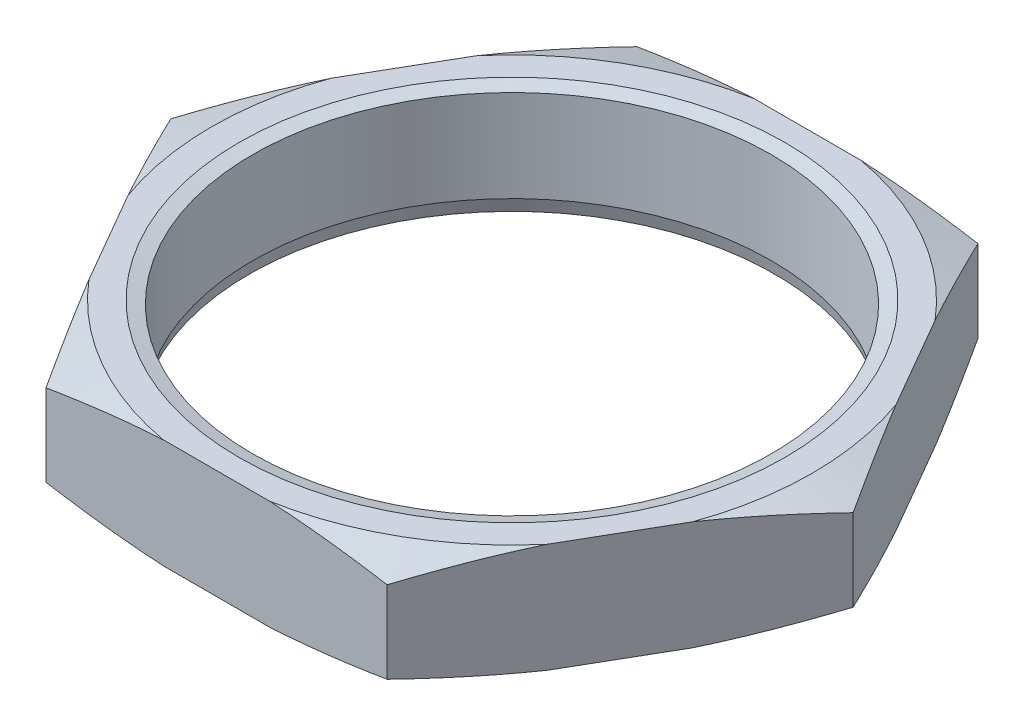
SolidWorks part; units mm, degrees
ref_plane "前视基准面" through (0, 0, 0) normal (0, 0, 1) x (1, 0, 0)
ref_plane "上视基准面" through (0, 0, 0) normal (0, 1, 0) x (1, 0, 0)
ref_plane "右视基准面" through (0, 0, 0) normal (1, 0, 0) x (0, 0, -1)
sketch "草图1" plane through (0, 0, 0) normal (0, 1, 0) x (1, 0, 0)
  line L1 (6.25, 10.8253) -> (-6.25, 10.8253)
  line L2 (-6.25, 10.8253) -> (-12.5, 0)
  line L3 (-12.5, 0) -> (-6.25, -10.8253)
  line L4 (-6.25, -10.8253) -> (6.25, -10.8253)
  line L5 (6.25, -10.8253) -> (12.5, 0)
  line L6 (12.5, 0) -> (6.25, 10.8253)
  circle A0 centre (0, 0) radius 12.5 construction
  circle A1 centre (0, 0) radius 9.5
  dimension "D1" = 25
  dimension "D3" = 19
  dimension "D2" = 21.6506
extrude "凸台-拉伸1" add sketch "草图1" along normal blind 4
sketch "草图2" plane through (0, 0, 0) normal (0, 0, 1) x (1, 0, 0)
  line L0 (11, 4) -> (12.5, 4)
  line L1 (-6.25, 4) -> (6.25, 4) construction
  line L2 (12.5, 4) -> (12.5, 3.5)
  line L4 (12.5, 3.5) -> (11, 4)
  line L5 (12.5, 0.5) -> (12.5, 0)
  line L6 (12.5, 0) -> (11, 0)
  line L7 (-6.25, 0) -> (6.25, 0) construction
  line L8 (11, 0) -> (12.5, 0.5)
  line L9 (0, 0) -> (0, 6.7072) construction
  line L10 (12.5, 4) -> (12.5, 0) construction
  dimension "D1" = 0.5
  dimension "D2" = 1.5
revolve "切除-旋转2" cut sketch "草图2" angle 360 about L9
chamfer "倒角1" distance 0.5 angle 15 2 edges at (0, 4, 9.5) (0, 0, 9.5)
